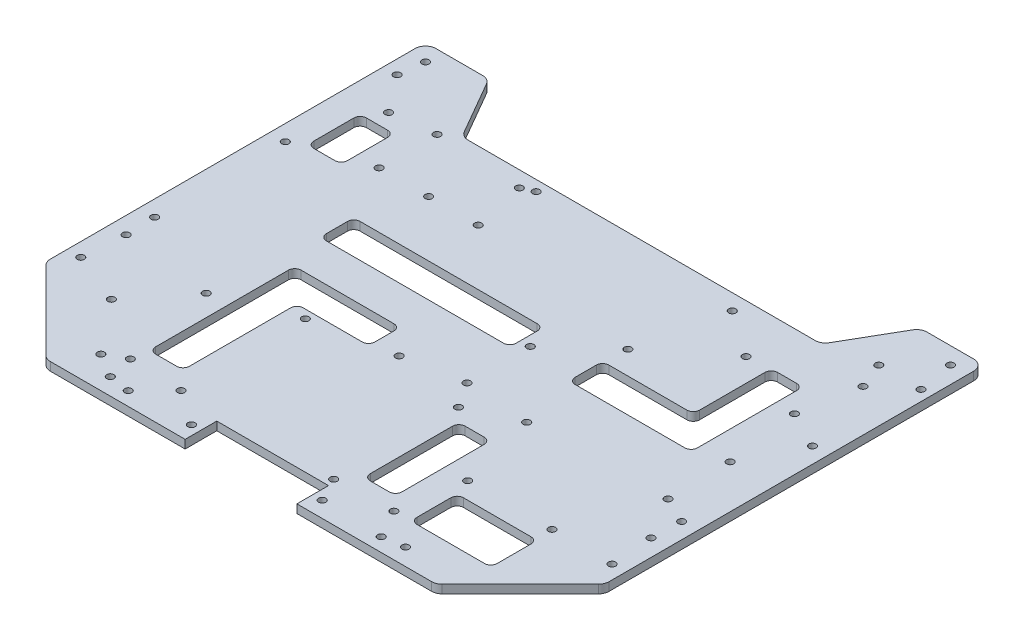
SolidWorks part; units mm, degrees
material "Acier non allié"
ref_plane "Front" through (0, 0, 0) normal (0, 0, 1) x (1, 0, 0)
ref_plane "Top" through (0, 0, 0) normal (0, 1, 0) x (1, 0, 0)
ref_plane "Right" through (0, 0, 0) normal (1, 0, 0) x (0, 0, -1)
sketch "Main scetch" plane through (0, 0, 0) normal (0, 1, 0) x (1, 0, 0)
  line L1 (0, 0) -> (132.5, 0) construction
  line L2 (0, 0) -> (0, 220) construction
  line L3 (0, 220) -> (132.5, 220) construction
  line L4 (132.5, 0) -> (132.5, 220) construction
  line L13 (-92.5, 0) -> (92.5, 0)
  line L14 (92.5, 0) -> (132.5, 40)
  line L15 (132.5, 40) -> (132.5, 220)
  line L16 (132.5, 220) -> (102.5, 220)
  line L17 (102.5, 220) -> (85.1795, 190)
  line L18 (85.1795, 190) -> (-85.1795, 190)
  line L19 (-102.5, 220) -> (-85.1795, 190)
  line L20 (-132.5, 220) -> (-102.5, 220)
  line L21 (-132.5, 40) -> (-132.5, 220)
  line L22 (-92.5, 0) -> (-132.5, 40)
  point P11 (0, 190)
  dimension "132.5" = 132.5
  dimension "D2" = 220
  dimension "D1" = 40
  dimension "D3" = 40
  dimension "D4" = 30
  dimension "D5" = 60
  dimension "D6" = 30
extrude "Main extrusion" add sketch "Main scetch" along normal blind 4
fillet "Congé1" radius 5 10 edges at (-132.5, 2, -40) (-92.5, 2, 0) (92.5, 2, 0) (132.5, 2, -40) (132.5, 2, -220) (102.5, 2, -220) (85.1795, 2, -190) (-85.1795, 2, -190) (-102.5, 2, -220) (-132.5, 2, -220)
sketch "Esquisse1" plane through (0, 4, 0) normal (0, 1, 0) x (1, 0, 0)
  line L0 (0, 0) -> (0, 218.5516) construction
  line L1 (132.5, 42.0711) -> (132.5, 215) construction
  line L2 (127.5, 220) -> (105.3868, 220) construction
  line L3 (-90.4289, 0) -> (90.4289, 0) construction
  circle A0 centre (70, 8) radius 1
  circle A1 centre (124.5, 70) radius 1
  circle A2 centre (124.5, 212) radius 1
  circle A3 centre (-124.5, 212) radius 1
  circle A4 centre (-124.5, 70) radius 1
  circle A5 centre (-70, 8) radius 1
  dimension "D1" = 2
  dimension "D2" = 2
  dimension "D3" = 2
  dimension "D4" = 8
  dimension "D5" = 8
  dimension "D6" = 8
  dimension "D7" = 8
  dimension "D8" = 70
  dimension "D9" = 70
extrude "Enlèv. mat.-Extru.1" cut sketch "Esquisse1" against normal through all
hole_wizard "Dégagement M31" positions "Esquisse2" profile "Esquisse3" hole size "M3" standard "ISO" end condition through all
sketch "Esquisse2" plane through (0, 4, 0) normal (0, 1, 0) x (1, 0, 0)
  point P0 (-124.5, 212)
  point P3 (-124.5, 70)
  point P6 (-70, 8)
  point P9 (70, 8)
  point P12 (124.5, 70)
  point P15 (124.5, 212)
sketch "Esquisse3" plane through (-124.5, 4, -212) normal (1, 0, 0) x (0, 0, 1)
  line L0 (0, 0) -> (0, 4)
  line L1 (0, 4) -> (1.7, 4)
  line L2 (1.7, 4) -> (1.7, 0)
  line L5 (1.7, 0) -> (0, 0)
  line L11 (0, -6.35) -> (0, 107.95) construction
  dimension "Diamètre du perçage jusqu'au prochain" = 3.4
  dimension "Profondeur du perçage jusqu'au prochain" = 4
sketch "Esquisse4" plane through (0, 4, 0) normal (0, 1, 0) x (1, 0, 0)
  line L0 (-132.5, 215) -> (-132.5, 42.0711) construction
  line L1 (-125, 146) -> (-125, 84) construction
  line L2 (82.2927, 190) -> (-82.2927, 190) construction
  line L3 (132.5, 42.0711) -> (132.5, 215) construction
  line L4 (-90.4289, 0) -> (90.4289, 0) construction
  line L5 (127.5, 220) -> (105.3868, 220) construction
  line L8 (-105.3868, 220) -> (-127.5, 220) construction
  line L9 (-31, 7.5) -> (31, 7.5) construction
  line L10 (125, 146) -> (125, 84) construction
  line L11 (-26.5, 0) -> (26.5, 0)
  line L12 (-26.5, 0) -> (-26.5, 15)
  line L13 (-26.5, 15) -> (26.5, 15)
  line L14 (26.5, 0) -> (26.5, 15)
  line L15 (50.5, 182.5) -> (112.5, 182.5) construction
  line L16 (-112.5, 182.5) -> (-50.5, 182.5) construction
  line L17 (-81.5, 65) -> (-81.5, 15) construction
  line L18 (-81.5, 40) -> (-101.5, 40) construction
  circle A1 centre (-68.5, 185) radius 1 construction
  circle A5 centre (72.5, 167) radius 1
  circle A6 centre (41.5, 142) radius 1
  circle A7 centre (107.5, 155) radius 1
  circle A8 centre (127.5, 195) radius 1
  circle A9 centre (112, 120) radius 1
  circle A10 centre (112.5, 90) radius 1
  circle A11 centre (17.2, 120) radius 1
  circle A12 centre (17.2, 90) radius 1
  circle A13 centre (47.5, 88) radius 1
  circle A14 centre (57.5, 50) radius 1
  circle A15 centre (97.5, 50) radius 1
  circle A16 centre (52.5, 20) radius 1
  circle A17 centre (-10, 85) radius 1
  circle A18 centre (-72.5, 20) radius 1
  circle A19 centre (107.5, 195) radius 1
  circle A23 centre (-47.5, 78) radius 1
  circle A24 centre (25.14, 78) radius 1
  circle A25 centre (-47.5, 19.07) radius 1
  circle A26 centre (25.1096, 18.82) radius 1
  circle A31 centre (-125, 146) radius 1
  circle A32 centre (-125, 84) radius 1
  circle A33 centre (-31, 7.5) radius 1
  circle A34 centre (31, 7.5) radius 1
  circle A35 centre (125, 146) radius 1
  circle A36 centre (125, 84) radius 1
  circle A37 centre (50.5, 182.5) radius 1
  circle A38 centre (112.5, 182.5) radius 1
  circle A39 centre (-112.5, 182.5) radius 1
  circle A40 centre (-50.5, 182.5) radius 1
  circle A41 centre (-45, 185) radius 1
  circle A42 centre (-45, 157.5) radius 1
  circle A43 centre (-68.5, 157.5) radius 1
  circle A44 centre (-92, 157.5) radius 1
  circle A45 centre (-92, 185) radius 1
  circle A46 centre (126, 50) radius 1.5
  circle A47 centre (-60, 6.5) radius 1.5
  circle A48 centre (60, 6.5) radius 1.5
  circle A49 centre (-126, 50) radius 1.5
  circle A50 centre (-126, 200) radius 1.5
  circle A51 centre (-81.5, 65) radius 1.5
  circle A52 centre (-81.5, 15) radius 1.5
  circle A53 centre (-101.5, 40) radius 1.5
  point P63 (-125, 115)
  point P69 (0, 7.5)
  point P74 (0, 15)
  point P79 (125, 115)
  dimension "D4" = 2
  dimension "D13" = 2
  dimension "D16" = 2
  dimension "D19" = 2
  dimension "D24" = 2
  dimension "D25" = 2
  dimension "D28" = 2
  dimension "D30" = 2
  dimension "D32" = 2
  dimension "D36" = 2
  dimension "D37" = 2
  dimension "D40" = 2
  dimension "D48" = 2
  dimension "D49" = 2
  dimension "D50" = 2
  dimension "D52" = 2
  dimension "D11" = 2
  dimension "D12" = 2
  dimension "D65" = 2
  dimension "D66" = 2
  dimension "D72" = 2
  dimension "D73" = 2
  dimension "D77" = 2
  dimension "D78" = 2
  dimension "D85" = 2
  dimension "D86" = 2
  dimension "D89" = 2
  dimension "D90" = 2
  dimension "D94" = 2
  dimension "D95" = 2
  dimension "D58" = 2
  dimension "D59" = 2
  dimension "D62" = 2
  dimension "D63" = 2
  dimension "D69" = 2
  dimension "D99" = 3
  dimension "D101" = 3
  dimension "D104" = 3
  dimension "D108" = 3
  dimension "D111" = 3
  dimension "D117" = 3
  dimension "D118" = 3
  dimension "D120" = 3
  dimension "D14" = 205
  dimension "D15" = 23
  dimension "D20" = 25
  dimension "D21" = 65
  dimension "D22" = 5
  dimension "D23" = 25
  dimension "D26" = 20.5
  dimension "D27" = 100
  dimension "D29" = 30
  dimension "D31" = 115.3
  dimension "D33" = 115.3
  dimension "D34" = 132
  dimension "D35" = 85
  dimension "D38" = 50
  dimension "D39" = 75
  dimension "D41" = 35
  dimension "D42" = 80
  dimension "D43" = 20
  dimension "D44" = 20
  dimension "D45" = 205
  dimension "D46" = 85
  dimension "D47" = 142.5
  dimension "D51" = 25
  dimension "D53" = 25
  dimension "D54" = 5
  dimension "D55" = 64
  dimension "D7" = 59.18
  dimension "D8" = 72.64
  dimension "D9" = 58.93
  dimension "D10" = 72.61
  dimension "D67" = 85
  dimension "D68" = 78
  dimension "D17" = 25
  dimension "D18" = 31
  dimension "D76" = 62
  dimension "D74" = 7.5
  dimension "D75" = 105
  dimension "D79" = 7.5
  dimension "D80" = 132.5
  dimension "D81" = 62
  dimension "D82" = 15
  dimension "D83" = 53
  dimension "D84" = 62
  dimension "D87" = 7.5
  dimension "D88" = 105
  dimension "D91" = 62
  dimension "D92" = 7.5
  dimension "D96" = 62
  dimension "D97" = 7.5
  dimension "D98" = 20
  dimension "D93" = 20
  dimension "D56" = 87.5
  dimension "D57" = 5
  dimension "D60" = 27.5
  dimension "D61" = 23.5
  dimension "D64" = 23.5
  dimension "D70" = 27.5
  dimension "D71" = 50
  dimension "D100" = 6.5
  dimension "D102" = 6.5
  dimension "D103" = 10
  dimension "D105" = 8
  dimension "D106" = 6.5
  dimension "D107" = 10
  dimension "D109" = 50
  dimension "D110" = 6.5
  dimension "D112" = 6.5
  dimension "D113" = 20
  dimension "D114" = 51
  dimension "D115" = 15
  dimension "D116" = 50
  dimension "D119" = 20
extrude "Enlèv. mat.-Extru.2" cut sketch "Esquisse4" against normal through all
hole_wizard "Dégagement M32" positions "Esquisse5" profile "Esquisse6" hole size "M3" standard "ISO" end condition through all
sketch "Esquisse5" plane through (0, 4, 0) normal (0, 1, 0) x (1, 0, 0)
  point P9 (17.2, 120)
  point P18 (41.5, 142)
  point P21 (72.5, 167)
  point P24 (107.5, 155)
  point P27 (127.5, 195)
  point P30 (112, 120)
  point P33 (112.5, 90)
  point P36 (47.5, 88)
  point P39 (17.2, 90)
  point P42 (57.5, 50)
  point P45 (97.5, 50)
  point P48 (-10, 85)
  point P51 (-72.5, 20)
  point P54 (52.5, 20)
  point P57 (107.5, 195)
  point P86 (-47.5, 78)
  point P89 (25.14, 78)
  point P92 (-47.5, 19.07)
  point P95 (25.1096, 18.82)
  point P114 (-125, 146)
  point P117 (-125, 84)
  point P121 (-31, 7.5)
  point P124 (31, 7.5)
  point P128 (125, 146)
  point P131 (125, 84)
  point P134 (-112.5, 182.5)
  point P137 (-50.5, 182.5)
  point P140 (50.5, 182.5)
  point P143 (112.5, 182.5)
  point P146 (-92, 185)
  point P149 (-92, 157.5)
  point P152 (-68.5, 157.5)
  point P155 (-45, 157.5)
  point P158 (-45, 185)
  point P161 (126, 50)
  point P164 (-60, 6.5)
  point P167 (60, 6.5)
  point P171 (-126, 200)
  point P177 (-126, 50)
  point P180 (-81.5, 65)
  point P183 (-81.5, 15)
  point P187 (-101.5, 40)
sketch "Esquisse6" plane through (17.2, 4, -120) normal (1, 0, 0) x (0, 0, 1)
  line L0 (0, 0) -> (0, 4)
  line L1 (0, 4) -> (1.7, 4)
  line L2 (1.7, 4) -> (1.7, 0)
  line L5 (1.7, 0) -> (0, 0)
  line L11 (0, -6.35) -> (0, 107.95) construction
  dimension "Diamètre du perçage jusqu'au prochain" = 3.4
  dimension "Profondeur du perçage jusqu'au prochain" = 4
sketch "Esquisse7" plane through (0, 4, 0) normal (0, 1, 0) x (1, 0, 0)
  line L0 (-90.4289, 0) -> (-26.5, 0) construction
  line L1 (-77.5, 131) -> (12.5, 131)
  line L2 (-77.5, 131) -> (-77.5, 115)
  line L3 (-77.5, 115) -> (12.5, 115)
  line L4 (12.5, 131) -> (12.5, 115)
  line L5 (-132.5, 215) -> (-132.5, 42.0711) construction
  line L8 (40.5, 115) -> (98.5, 115)
  line L10 (132.5, 42.0711) -> (132.5, 215) construction
  line L11 (40.5, 115) -> (40.5, 131)
  line L12 (83.5, 168) -> (98.5, 168)
  line L13 (83.5, 168) -> (83.5, 131)
  line L15 (98.5, 168) -> (98.5, 115)
  line L16 (40.5, 131) -> (83.5, 131)
  line L17 (-105.3868, 220) -> (-127.5, 220) construction
  line L18 (60.5, 42) -> (98.5, 42)
  line L19 (60.5, 42) -> (60.5, 20)
  line L20 (60.5, 20) -> (98.5, 20)
  line L21 (98.5, 42) -> (98.5, 20)
  line L22 (-118.5, 175) -> (-102.5, 175)
  line L23 (-118.5, 175) -> (-118.5, 150)
  line L24 (-118.5, 150) -> (-102.5, 150)
  line L25 (-102.5, 175) -> (-102.5, 150)
  line L27 (-71.5, 28) -> (-55.5, 28)
  line L28 (-71.5, 28) -> (-71.5, 83)
  line L30 (-55.5, 28) -> (-55.5, 82)
  line L31 (31.5, 71.82) -> (46.5, 71.82)
  line L32 (31.5, 71.82) -> (31.5, 26.82)
  line L33 (31.5, 26.82) -> (46.5, 26.82)
  line L34 (46.5, 71.82) -> (46.5, 26.82)
  line L35 (-71.5, 97) -> (-21.5, 97)
  line L36 (-71.5, 97) -> (-71.5, 83)
  line L37 (-55.5, 82) -> (-21.5, 82)
  line L38 (-21.5, 97) -> (-21.5, 82)
  circle A0 centre (-72.5, 20) radius 1.7 construction
  circle A1 centre (-47.5, 78) radius 1.7 construction
  circle A2 centre (25.1096, 18.82) radius 1.7 construction
  circle A3 centre (52.5, 20) radius 1.7 construction
  dimension "D19" = 8
  dimension "D20" = 8
  dimension "D24" = 15
  dimension "D1" = 90
  dimension "D2" = 16
  dimension "D3" = 131
  dimension "D4" = 55
  dimension "D5" = 16
  dimension "D6" = 53
  dimension "D7" = 43
  dimension "D8" = 115
  dimension "D9" = 72
  dimension "D10" = 38
  dimension "D11" = 34
  dimension "D12" = 15
  dimension "D13" = 22
  dimension "D14" = 20
  dimension "D15" = 30
  dimension "D16" = 70
  dimension "D17" = 16
  dimension "D18" = 25
  dimension "D21" = 16
  dimension "D22" = 55
  dimension "D23" = 8
  dimension "6" = 6
  dimension "D25" = 45
  dimension "D26" = 50
  dimension "D27" = 54
  dimension "D28" = 15
extrude "Enlèv. mat.-Extru.3" cut sketch "Esquisse7" against normal up to surface (4 mm away) up to face at (17.2, 0, -118.3)
fillet "Congé2" radius 3 28 edges at (60.5, 2, -42) (60.5, 2, -20) (98.5, 2, -20) (98.5, 2, -42) (98.5, 2, -168) (98.5, 2, -115) (83.5, 2, -168) (40.5, 2, -131) (83.5, 2, -131) (40.5, 2, -115) (-77.5, 2, -115) (12.5, 2, -115) (12.5, 2, -131) (-77.5, 2, -131) (-118.5, 2, -150) (-102.5, 2, -150) (-102.5, 2, -175) (-118.5, 2, -175) (-55.5, 2, -28) (-71.5, 2, -28) (46.5, 2, -26.82) (31.5, 2, -26.82) (46.5, 2, -71.82) (31.5, 2, -71.82) (-21.5, 2, -82) (-21.5, 2, -97) (-55.5, 2, -82) (-71.5, 2, -97)
equation "\"WIDTH\"= 300mm'Total width of the robot"
equation "\"LENGTH\"= 220mm'Total length of the robot"
equation "\"D2@Main scetch\" = \"LENGTH\""
equation "\"CUT_DEPTH\"= 45mm'Depth of the cut on the edges of the plate"
equation "\"Plate_th\"= 3mm'Thickness of the plate"
equation "\"D1\"= \"Plate_th\""
equation "\"D47@Esquisse4\"=(80+205)/2"
